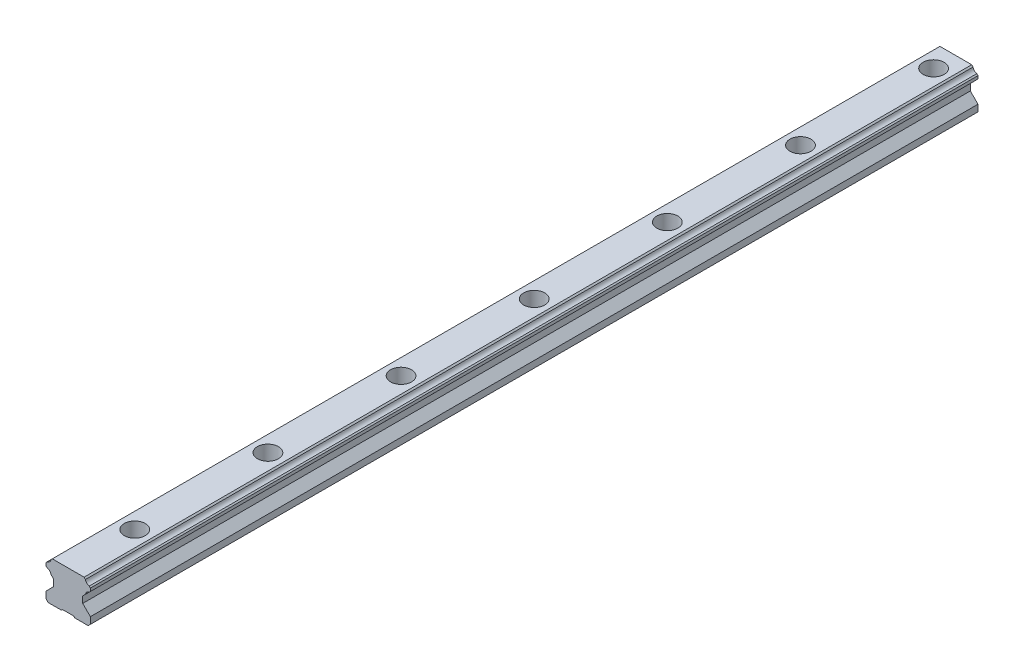
SolidWorks part; units mm, degrees
material "Plain Carbon Steel"
ref_plane "Front Plane" through (0, 0, 0) normal (0, 0, 1) x (1, 0, 0)
ref_plane "Top Plane" through (0, 0, 0) normal (0, 1, 0) x (1, 0, 0)
ref_plane "Right Plane" through (0, 0, 0) normal (1, 0, 0) x (0, 0, -1)
sketch "Sketch1" plane through (0, 0, 0) normal (0, 0, 1) x (1, 0, 0)
  line L0 (-10, -10.4945) -> (-10, -13.4946)
  line L1 (-10, -13.4946) -> (-9, -14.4946)
  line L2 (-9, -14.4946) -> (-3, -14.4946)
  line L3 (-3, -14.4946) -> (-2.5, -13.9946)
  line L4 (-2.5, -13.9946) -> (2.5, -13.9946)
  line L5 (6.55, -7.0447) -> (10, -10.4945)
  line L6 (6.55, -4.1154) -> (6.55, -7.0447)
  line L7 (7.7679, -2.8995) -> (6.55, -4.1154)
  line L8 (10, -0.6654) -> (9.4727, -1.1802)
  line L9 (10, 0.6654) -> (10, -0.6654)
  line L10 (9.4727, 1.1928) -> (10, 0.6654)
  line L11 (7.16, 3.5054) -> (7.7679, 2.8975)
  line L12 (3, -14.4946) -> (2.5, -13.9946)
  line L13 (9, -14.4946) -> (3, -14.4946)
  line L14 (10, -13.4946) -> (9, -14.4946)
  line L15 (10, -10.4945) -> (10, -13.4946)
  line L16 (7.16, 3.5054) -> (-7.16, 3.5054)
  line L17 (-7.16, 3.5054) -> (-7.7679, 2.8975)
  line L18 (-9.4727, 1.1928) -> (-10, 0.6654)
  line L19 (-10, 0.6654) -> (-10, -0.6654)
  line L20 (-10, -0.6654) -> (-9.4727, -1.1802)
  line L21 (-7.7679, -2.8995) -> (-6.55, -4.1154)
  line L22 (-6.55, -4.1154) -> (-6.55, -7.0447)
  line L23 (-6.55, -7.0447) -> (-10, -10.4945)
  line L24 (0, -14.4946) -> (0, -13.9946) construction
  line L25 (0, -13.9946) -> (0, 3.5054) construction
  line L26 (55, 0) -> (-55, 0) construction
  arc A0 (9.4727, -1.1802) -> (7.7679, -2.8995) centre (9.8039, -3.2134) ccw
  arc A1 (7.7679, 2.8975) -> (9.4727, 1.1928) centre (9.8015, 3.2263) ccw
  arc A2 (-7.7679, 2.8975) -> (-9.4727, 1.1928) centre (-9.8015, 3.2263) cw
  arc A3 (-9.4727, -1.1802) -> (-7.7679, -2.8995) centre (-9.8039, -3.2134) cw
  point P38 (10, 0)
  dimension "D17" = 2.06
  dimension "D1" = 20
  dimension "D2" = 1
  dimension "D3" = 1
  dimension "D4" = 0.5
  dimension "D5" = 0.5
  dimension "D6" = 6
  dimension "D7" = 18
  dimension "D8" = 4.0001
  dimension "D9" = 10.55
  dimension "D10" = 13.1001
  dimension "D11" = 15.5359
  dimension "D12" = 0.6079
  dimension "D13" = 0.6079
  dimension "D14" = 17.5
  dimension "D15" = 0.5273
  dimension "D16" = 0.5273
  dimension "D18" = 1.2159
  dimension "D19" = 0.5148
  dimension "D20" = 6.4049
  dimension "D21" = 2.84
  dimension "D22" = 4.1708
extrude "Boss-Extrude1" add sketch "Sketch1" against normal mid plane 400
sketch "Sketch2" plane through (0, 0, 0) normal (1, 0, 0) x (0, 0, -1)
  line L0 (-170, 3.5054) -> (-170, -14.4946)
  line L1 (200, 3.5054) -> (-200, 3.5054) construction
  line L2 (200, -14.4946) -> (-200, -14.4946) construction
  line L3 (-170, -14.4946) -> (-173, -14.4946)
  line L4 (-173, -14.4946) -> (-173, -4.9946)
  line L5 (-173, -4.9946) -> (-174.75, -4.9946)
  line L6 (-174.75, -4.9946) -> (-174.75, 3.5054)
  line L7 (-174.75, 3.5054) -> (-170, 3.5054)
  line L8 (-200, -7.0447) -> (-200, -4.1154) construction
  point P12 (-200, -5.58)
  dimension "D1" = 3
  dimension "D2" = 4.75
  dimension "D3" = 8.5
  dimension "D4" = 30
revolve "Cut-Revolve1" cut sketch "Sketch2" angle 360 about L0
pattern_linear "LPattern1" count 7 spacing 60 along (0, 0, -1) of "Cut-Revolve1"
